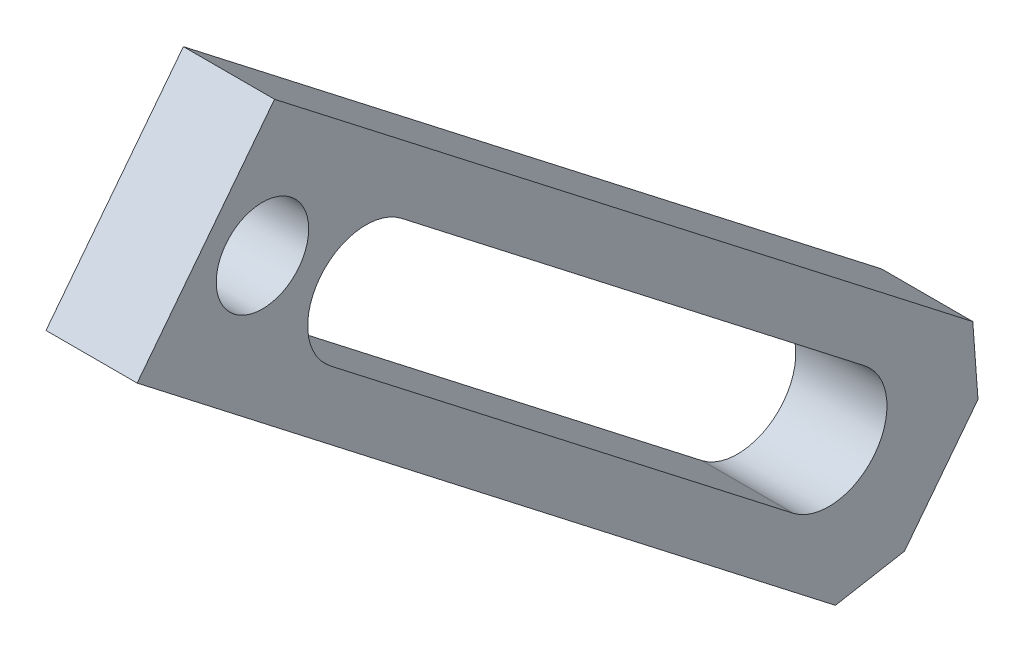
SolidWorks part; units mm, degrees
ref_plane "Front Plane" through (0, 0, 0) normal (0, 0, 1) x (1, 0, 0)
ref_plane "Top Plane" through (0, 0, 0) normal (0, 1, 0) x (1, 0, 0)
ref_plane "Right Plane" through (0, 0, 0) normal (1, 0, 0) x (0, 0, -1)
sketch "Sketch1" plane through (0, 0, 0) normal (1, 0, 0) x (0, 0, -1)
  line L0 (253.6693, 98.4347) -> (277.7386, 129.4643)
  line L1 (277.7386, 129.4643) -> (400.0729, 34.5724)
  line L2 (400.0729, 34.5724) -> (400.988, 22.3004)
  line L3 (400.988, 22.3004) -> (394.5529, 14.004)
  line L4 (394.5529, 14.004) -> (388.1176, 5.7079)
  line L5 (388.1176, 5.7079) -> (376.0036, 3.5425)
  line L6 (376.0036, 3.5425) -> (253.6693, 98.4347)
  line L7 (287.4978, 84.1309) -> (368.5814, 21.2359)
  line L8 (300.0057, 100.2558) -> (381.0894, 37.3611)
  arc A0 (381.0894, 37.3611) -> (368.5814, 21.2359) centre (374.8354, 29.2985) cw
  arc A1 (287.4978, 84.1309) -> (300.0057, 100.2558) centre (293.7518, 92.1933) cw
  circle A2 centre (275.621, 106.806) radius 8.1
  point P15 (269.068, 111.5672)
extrude "Boss-Extrude1" add sketch "Sketch1" against normal blind 15.9723
